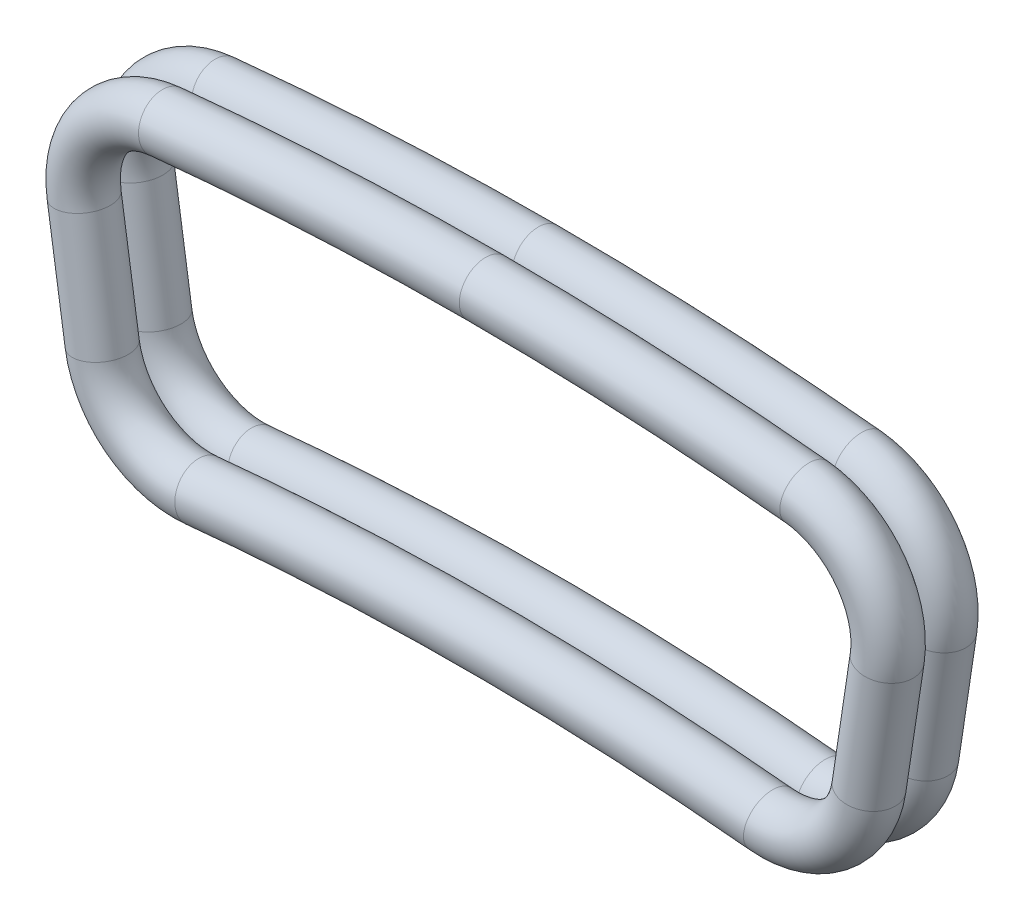
SolidWorks part; units mm, degrees
material "Copper"
ref_plane "Front Plane" through (0, 0, 0) normal (0, 0, 1) x (1, 0, 0)
ref_plane "Top Plane" through (0, 0, 0) normal (0, 1, 0) x (1, 0, 0)
ref_plane "Right Plane" through (0, 0, 0) normal (1, 0, 0) x (0, 0, -1)
sketch "Sketch1" plane through (0, 0, 0) normal (0, 0, 1) x (1, 0, 0)
  line L0 (11.8453, 90.7593) -> (12.404, 94.466)
  line L1 (-12.404, 94.466) -> (-11.8453, 90.7593)
  line L2 (11.0404, 90.8806) -> (11.5991, 94.5874)
  line L3 (-11.5991, 94.5874) -> (-11.0404, 90.8806)
  line L4 (11.0404, 90.8806) -> (11.5991, 94.5874) construction
  line L5 (-11.5991, 94.5874) -> (-11.0404, 90.8806) construction
  arc A0 (12.404, 94.466) -> (9.9053, 97.6851) centre (9.6214, 94.8854) ccw
  arc A1 (9.9053, 97.6851) -> (-9.9053, 97.6851) centre (0, 0) ccw
  arc A2 (-9.9053, 97.6851) -> (-12.404, 94.466) centre (-9.6214, 94.8854) ccw
  arc A3 (-11.8453, 90.7593) -> (-8.7844, 88.3785) centre (-9.0627, 91.1787) ccw
  arc A4 (8.7844, 88.3785) -> (-8.7844, 88.3785) centre (0, 0) ccw
  arc A5 (8.7844, 88.3785) -> (11.8453, 90.7593) centre (9.0627, 91.1787) ccw
  arc A6 (11.5991, 94.5874) -> (9.8232, 96.8752) centre (9.6214, 94.8854) ccw
  arc A7 (9.8232, 96.8752) -> (-9.8232, 96.8752) centre (0, 0) ccw
  arc A8 (-9.8232, 96.8752) -> (-11.5991, 94.5874) centre (-9.6214, 94.8854) ccw
  arc A9 (-11.0404, 90.8806) -> (-8.8649, 89.1885) centre (-9.0627, 91.1787) ccw
  arc A10 (8.8649, 89.1885) -> (-8.8649, 89.1885) centre (0, 0) ccw
  arc A11 (8.8649, 89.1885) -> (11.0404, 90.8806) centre (9.0627, 91.1787) ccw
  arc A12 (11.5991, 94.5874) -> (9.8232, 96.8752) centre (9.6214, 94.8854) ccw construction
  arc A13 (9.8232, 96.8752) -> (-9.8232, 96.8752) centre (0, 0) ccw construction
  arc A14 (-9.8232, 96.8752) -> (-11.5991, 94.5874) centre (-9.6214, 94.8854) ccw construction
  arc A15 (-11.0404, 90.8806) -> (-8.8649, 89.1885) centre (-9.0627, 91.1787) ccw construction
  arc A16 (8.8649, 89.1885) -> (-8.8649, 89.1885) centre (0, 0) ccw construction
  arc A17 (8.8649, 89.1885) -> (11.0404, 90.8806) centre (9.0627, 91.1787) ccw construction
  dimension "D1" = 0
  dimension "D2" = 0.814
ref_plane "Plane1" through (0, 0, -2.386) normal (0, 0, 1) x (1, 0, 0)
sketch "Sketch3" plane through (0, 0, -2.386) normal (0, 0, 1) x (1, 0, 0)
  line L0 (11.8453, 90.7593) -> (12.404, 94.466) construction
  line L1 (-12.404, 94.466) -> (-11.8453, 90.7593) construction
  line L2 (11.8453, 90.7593) -> (12.404, 94.466)
  line L3 (-12.404, 94.466) -> (-11.8453, 90.7593)
  arc A0 (12.404, 94.466) -> (9.9053, 97.6851) centre (9.6214, 94.8854) ccw construction
  arc A1 (8.7844, 88.3785) -> (11.8453, 90.7593) centre (9.0627, 91.1787) ccw construction
  arc A2 (8.7844, 88.3785) -> (-8.7844, 88.3785) centre (0, 0) ccw construction
  arc A3 (-11.8453, 90.7593) -> (-8.7844, 88.3785) centre (-9.0627, 91.1787) ccw construction
  arc A4 (-9.9053, 97.6851) -> (-12.404, 94.466) centre (-9.6214, 94.8854) ccw construction
  arc A5 (9.9053, 97.6851) -> (-9.9053, 97.6851) centre (0, 0) ccw construction
  arc A6 (12.404, 94.466) -> (9.9053, 97.6851) centre (9.6214, 94.8854) ccw
  arc A7 (8.7844, 88.3785) -> (11.8453, 90.7593) centre (9.0627, 91.1787) ccw
  arc A8 (8.7844, 88.3785) -> (-8.7844, 88.3785) centre (0, 0) ccw
  arc A9 (-11.8453, 90.7593) -> (-8.7844, 88.3785) centre (-9.0627, 91.1787) ccw
  arc A10 (-9.9053, 97.6851) -> (-12.404, 94.466) centre (-9.6214, 94.8854) ccw
  arc A11 (9.9053, 97.6851) -> (-9.9053, 97.6851) centre (0, 0) ccw
sketch "Sketch4" plane through (0, 0, 0) normal (1, 0, 0) x (0, 0, -1)
  circle A0 centre (2.386, 98.186) radius 0.814
  dimension "D1" = 1.628
sweep "Sweep2" add profiles "Sketch4" path "Sketch3"
pattern_linear "LPattern1" count 2 spacing 1.628 along (0, 0, 1) of bodies 102
